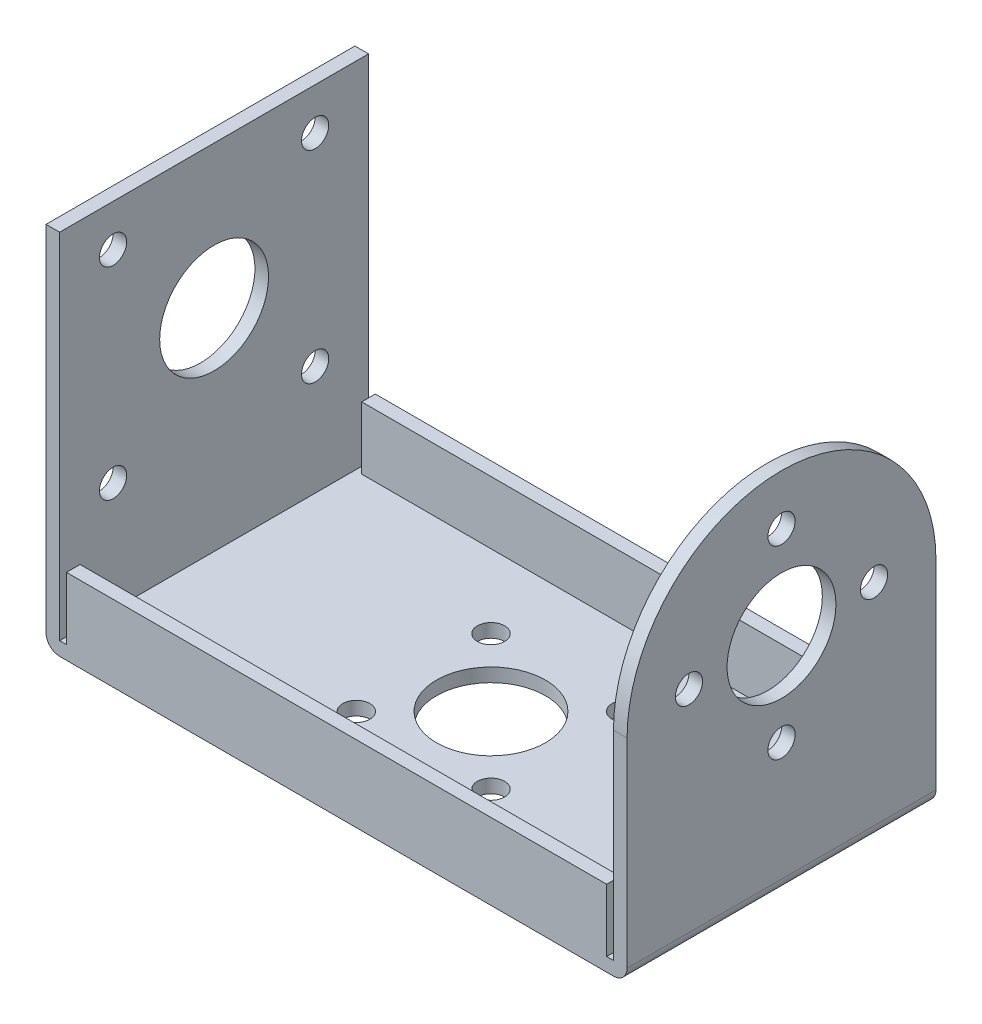
SolidWorks part; units mm, degrees
ref_plane "Front Plane" through (0, 0, 0) normal (0, 0, 1) x (1, 0, 0)
ref_plane "Top Plane" through (0, 0, 0) normal (0, 1, 0) x (1, 0, 0)
ref_plane "Right Plane" through (0, 0, 0) normal (1, 0, 0) x (0, 0, -1)
sketch "Sketch1" plane through (0, 0, 0) normal (0, 1, 0) x (1, 0, 0)
  line L0 (0, 0) -> (42.7, 0)
  line L1 (42.7, 0) -> (42.7, 22.7)
  line L2 (42.7, 22.7) -> (0, 22.7)
  line L3 (0, 22.7) -> (0, 0)
  line L4 (21.35, 22.7) -> (21.35, 0) construction
  line L5 (0, 11.35) -> (42.7, 11.35) construction
  line L6 (10, 0) -> (32.7, 22.7) construction
  line L7 (32.7, 0) -> (10, 22.7) construction
  line L8 (24.1784, 14.1784) -> (26.2997, 16.2997) construction
  circle A0 centre (21.35, 11.35) radius 4
  circle A1 centre (26.2997, 16.2997) radius 1
  circle A2 centre (26.2997, 6.4003) radius 1
  circle A3 centre (16.4003, 6.4003) radius 1
  circle A4 centre (16.4003, 16.2997) radius 1
  point P27 (21.35, 11.35)
  dimension "D1" = 4
extrude "Boss-Extrude1" add sketch "Sketch1" along normal blind 1
sketch "Sketch2" plane through (0, 1, 0) normal (0, 1, 0) x (1, 0, 0)
  line L0 (0, 0) -> (0, 22.7)
  line L1 (0, 22.7) -> (1, 22.7)
  line L2 (42.7, 22.7) -> (0, 22.7) construction
  line L3 (1, 22.7) -> (1, 0)
  line L4 (0, 0) -> (42.7, 0) construction
  line L5 (1, 0) -> (0, 0)
  line L6 (42.7, 22.7) -> (42.7, 0)
  line L7 (42.7, 0) -> (41.7, 0)
  line L8 (41.7, 0) -> (41.7, 22.7)
  line L9 (41.7, 22.7) -> (42.7, 22.7)
extrude "Boss-Extrude2" add sketch "Sketch2" along normal blind 26
sketch "Sketch3" plane through (0, 1, 0) normal (0, 1, 0) x (1, 0, 0)
  line L0 (1, 22.7) -> (1.5, 22.7) construction
  line L1 (41.7, 22.7) -> (1, 22.7) construction
  line L2 (1.5, 22.7) -> (41.2, 22.7)
  line L3 (41.2, 22.7) -> (41.2, 21.7)
  line L4 (41.2, 21.7) -> (1.5, 21.7)
  line L5 (1.5, 21.7) -> (1.5, 22.7)
  line L6 (17.35, 11.35) -> (25.35, 11.35) construction
  line L7 (41.2, 1) -> (1.5, 1)
  line L8 (41.2, 0) -> (41.2, 1)
  line L9 (1.5, 0) -> (41.2, 0)
  line L10 (1.5, 1) -> (1.5, 0)
  circle A0 centre (21.35, 11.35) radius 4 construction
extrude "Boss-Extrude3" add sketch "Sketch3" along normal blind 4.6
fillet "Fillet2" radius 1 2 edges at (42.7, 0, -11.35) (0, 0, -11.35)
sketch "Sketch4" plane through (0, 0, 0) normal (-1, 0, 0) x (0, 0, 1)
  line L0 (-11.35, 27) -> (-11.35, 1) construction
  line L1 (-22.7, 27) -> (0, 27) construction
  line L2 (-22.7, 1) -> (0, 1) construction
  line L3 (-11.35, 27) -> (-11.35, 16.5) construction
  line L4 (0, 5.15) -> (-21.85, 27) construction
  line L5 (-22.7, 5.15) -> (-0.85, 27) construction
  line L6 (-22.7, 1) -> (-22.7, 27)
  line L7 (-22.7, 27) -> (0, 27)
  line L8 (0, 27) -> (0, 1)
  line L9 (-8.5216, 19.3284) -> (-3.9254, 23.9246) construction
  circle A0 centre (-11.35, 16.5) radius 4
  circle A1 centre (-3.9254, 23.9246) radius 1
  circle A2 centre (-3.9254, 9.0754) radius 1
  circle A3 centre (-18.7746, 9.0754) radius 1
  circle A4 centre (-18.7746, 23.9246) radius 1
  point P32 (-11.35, 16.5)
  dimension "D1" = 4
extrude "Cut-Extrude1" cut sketch "Sketch4" against normal blind 1 contours A0 | A4 | A1 | A2 | A3
sketch "Sketch5" plane through (42.7, 0, 0) normal (1, 0, 0) x (0, 0, -1)
  line L0 (11.35, 27) -> (11.35, 1) construction
  line L1 (0, 27) -> (22.7, 27) construction
  line L2 (0, 1) -> (22.7, 1) construction
  line L3 (11.35, 27) -> (11.35, 15.65) construction
  line L4 (11.35, 27) -> (11.35, 16.5) construction
  line L5 (0, 1) -> (0, 27)
  line L6 (0, 27) -> (22.7, 27)
  line L7 (22.7, 27) -> (22.7, 1)
  line L8 (11.35, 20.5) -> (11.35, 23.3) construction
  arc A0 (22.7, 15.65) -> (0, 15.65) centre (11.35, 15.65) ccw
  circle A1 centre (11.35, 16.5) radius 4
  circle A2 centre (11.35, 23.3) radius 1
  circle A3 centre (18.15, 16.5) radius 1
  circle A4 centre (11.35, 9.7) radius 1
  circle A5 centre (4.55, 16.5) radius 1
  point P31 (11.35, 16.5)
  line M4 (0, 27) -> (0, 1)
  line M7 (22.7, 27) -> (0, 27)
  dimension "D1" = 4
extrude "Cut-Extrude2" cut sketch "Sketch5" against normal blind 1 contours A0 L6 M4 | A0 L7 M7 | A2 | A1 | A3 | A4 | A5
